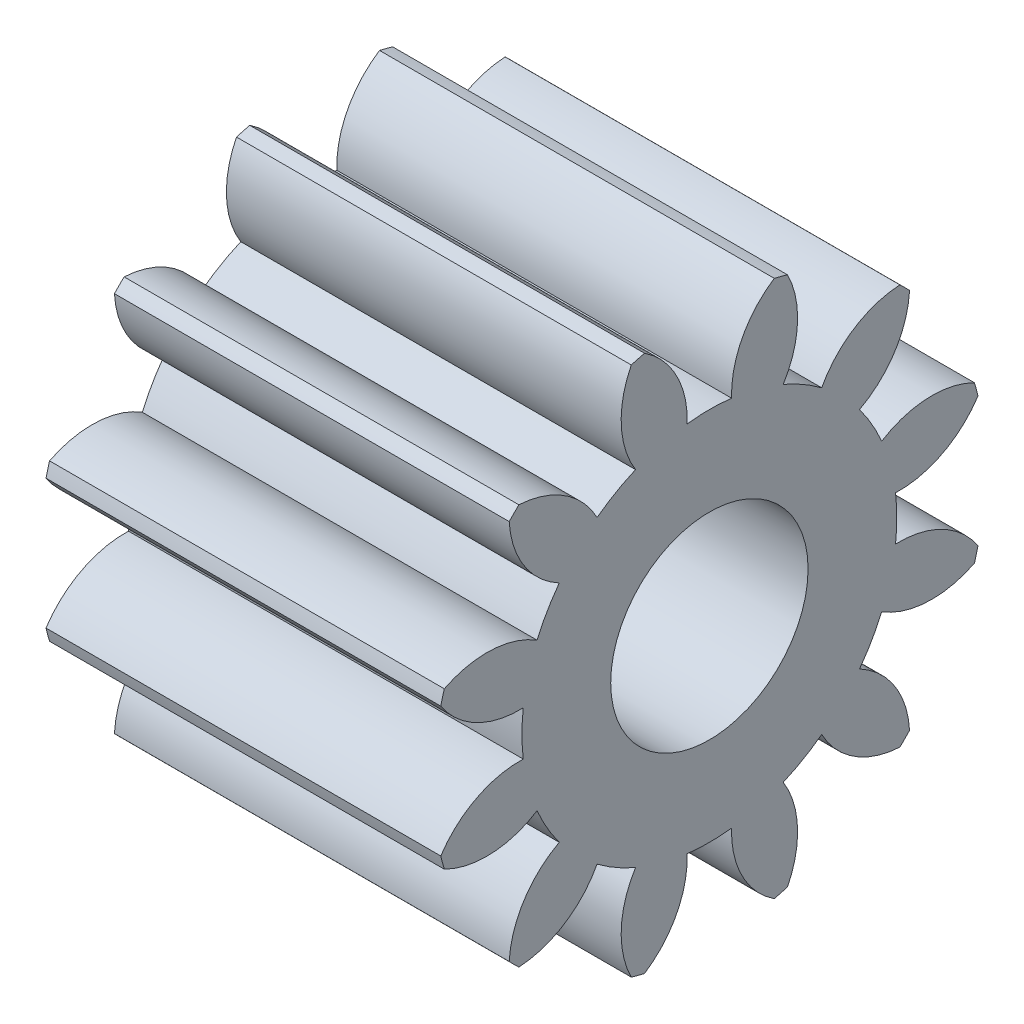
SolidWorks part; units mm, degrees
ref_plane "Plane1" through (0, 0, 0) normal (0, 0, 1) x (1, 0, 0)
ref_plane "Plane2" through (0, 0, 0) normal (0, 1, 0) x (1, 0, 0)
ref_plane "Plane3" through (0, 0, 0) normal (1, 0, 0) x (0, 0, -1)
sketch "HoldingSke" plane through (0, 0, 0) normal (0, 1, 0) x (1, 0, 0)
  line L0 (0, 0) -> (0.9781, -0.2079)
  line L1 (-15, 0) -> (100, 0) construction
  line L2 (0, 0) -> (-2.1039, 2.3779)
  line L3 (0, 0) -> (-11.863, 4.5341)
  line L4 (0, 0) -> (8.4473, 1.7955)
  line L5 (0, 0) -> (-46.8476, -17.4728)
  line L6 (0, 0) -> (-8.2896, -5.593)
  line L7 (-2.1039, 2.3779) -> (8.6586, 51.2059)
  line L8 (-76.2, 54.61) -> (-75.3, 54.61)
  line L9 (-71.009, 38.7566) -> (-53.1078, 45.2721)
  line L10 (-76.2, 71.12) -> (104.1128, 71.12)
  line L11 (0, 0) -> (-10, 0)
  line L12 (-76.2, 101.6) -> (-76.162, 101.6)
  line L13 (24.9733, 27.94) -> (52.9518, 28.4284)
  line L14 (24.9733, 27.94) -> (24.9743, 27.94)
  line L15 (24.9733, 27.94) -> (100.4006, 29.5858)
  line L16 (-63.627, -1) -> (-12.827, -1)
  circle A0 centre (0, 0) radius 2.5
  circle A1 centre (0, 0) radius 4.749
  circle A2 centre (0, 0) radius 37.5
  circle A3 centre (0, 0) radius 2.5
  dimension "MHD" = 9.498
  dimension "Hub_dia" = 75
  dimension "Bore" = 5
  dimension "MBD" = 5
  dimension "Num_teeth" = 12
  dimension "Pitch" = 1
  dimension "Overall_len" = 50
  dimension "Show_teeth" = 12
  dimension "Thickness" = 10
  dimension "OAL" = 50.0001
  dimension "T_dim" = 0.9
  dimension "Ap" = 20
  dimension "H" = 19.05
  dimension "Pitch_radius" = 180.3128
  dimension "Width" = 10
  dimension "Backlash" = 0.038
  dimension "Addendum_fac" = 1
  dimension "Dedendum_fac" = 1.25
  dimension "Clearance_fac" = 0.25
  dimension "Dedendum_add" = 0.001
  dimension "Module" = 1
sketch "BasProSke" plane through (0, 0, 0) normal (0, 1, 0) x (1, 0, 0)
  line L0 (-10, 0) -> (60, 0) construction
  line L1 (0, 0) -> (0, 7)
  line L2 (0, 0) -> (10, 0)
  line L3 (10, 0) -> (10, 7)
  line L4 (10, 7) -> (0, 7)
  dimension "Thickness" = 10
  dimension "Diameter" = 14
revolve "Base-Revolve" add sketch "BasProSke" angle 360 about L0
sketch "TooCutSke" plane through (0, 0, 0) normal (1, 0, 0) x (0, 0, -1)
  line L1 (0, 0) -> (0, 107) construction
  line L2 (0, 0) -> (-0.8496, 5.9395) construction
  line L3 (0, 0) -> (-3.0836, 11.5081) construction
  line L4 (-0.8496, 5.9395) -> (-1.5418, 5.7541) construction
  arc A0 (0.5622, 4.7156) -> (-0.5622, 4.7156) centre (0, 0) ccw
  arc A1 (1.6729, 6.8233) -> (-1.6729, 6.8233) centre (0, 0) ccw
  circle A2 centre (0, 0) radius 6 construction
  circle A3 centre (0, 0) radius 5.6382 construction
  arc A4 (-0.5622, 4.7156) -> (-1.6729, 6.8233) centre (-2.9608, 4.7982) ccw
  arc A5 (1.6729, 6.8233) -> (0.5622, 4.7156) centre (2.9608, 4.7982) ccw
  dimension "Root_dia" = 9.498
  dimension "Overcut_dia" = 14.0508
  dimension "Pitch_dia" = 12
  dimension "Base_dia" = 11.2763
  dimension "Flank_rad" = 2.4
  dimension "Half_ang" = 15
  dimension "Half_CT" = 0.7167
extrude "ToothCut" cut sketch "TooCutSke" along normal through all
fillet "Breaks" [suppressed] radius 0.02
fillet "RootFillets" [suppressed] radius 0.251
pattern_circular "TeethCuts" count 12 every 30 about axis through (-10, 0, 0) along (1, 0, 0) of "ToothCut", "RootFillets", "Breaks"
sketch "HubNeaOneSke" plane through (0, 0, 0) normal (-1, 0, 0) x (0, 0, 1)
  circle A0 centre (0, 0) radius 4.749
  dimension "Diameter" = 9.498
extrude "HubNearOne" [suppressed] add sketch "HubNeaOneSke" along normal blind 40.0001
sketch "HubNeaBotSke" plane through (0, 0, 0) normal (-1, 0, 0) x (0, 0, 1)
  circle A0 centre (0, 0) radius 4.749
  dimension "Diameter" = 9.498
extrude "HubNearBoth" [suppressed] add sketch "HubNeaBotSke" along normal blind 20
ref_plane "FarPln" through (10, 0, 0) normal (1, 0, 0) x (0, 0, -1)
sketch "HubFarSke" plane through (10, 0, 0) normal (1, 0, 0) x (0, 0, -1)
  circle A0 centre (0, 0) radius 4.749
  dimension "Diameter" = 9.498
extrude "HubFar" [suppressed] add sketch "HubFarSke" along normal blind 20
sketch "BorSke" plane through (0, 0, 0) normal (1, 0, 0) x (0, 0, -1)
  circle A0 centre (0, 0) radius 2.5
  dimension "Diameter" = 5
extrude "Bore" cut sketch "BorSke" along normal mid plane 100.0001
sketch "KeySke" plane through (0, 0, 0) normal (1, 0, 0) x (0, 0, -1)
  line L0 (-1, 0) -> (-1, 3.4)
  line L1 (-1, 3.4) -> (1, 3.4)
  line L2 (1, 3.4) -> (1, 0)
  line L3 (0, 0) -> (0, 34) construction
  line L4 (-1, 0) -> (1, 0)
  dimension "Offset" = 3.4
  dimension "Width" = 2
extrude "Keyway" [suppressed] cut sketch "KeySke" along normal mid plane 100.0001
pattern_circular "Keyway2" [suppressed] count 2 every 90 about axis through (-10, 0, 0) along (1, 0, 0)
equation "' \"Module@HoldingSke\" = 6.35"
equation "' \"Num_teeth@HoldingSke\" = 12"
equation "' \"Ap@HoldingSke\" =  20"
equation "' \"Ap@HoldingSke\" = 20"
equation "' \"Width@HoldingSke\" = 0.5 * 25.4"
equation "' \"Hub_dia@HoldingSke\"= 1 * 25.4"
equation "' \"Hub_dia@HoldingSke\" = 1 * 25.4"
equation "' \"Overall_len@HoldingSke\" = 1.0 * 25.4"
equation "' \"Bore@HoldingSke\" = 0.75 * 25.4"
equation "' \"T_dim@HoldingSke\" = 0.1 * 25.4"
equation "' \"Width@KeySke\" = 0.25 * 25.4"
equation "' \"Show_teeth@HoldingSke\" = 13"
equation "' \"Backlash@HoldingSke\" = 0.009 * 25.4"
equation "' \"Addendum_fac@HoldingSke\" = 1.0"
equation "' \"Dedendum_fac@HoldingSke\" = 1.25"
equation "' \"Dedendum_add@HoldingSke\" = 0.00005 * 25.4"
equation "' \"Clearance_fac@HoldingSke\" = 0.25"
equation "\"Pitch@HoldingSke\" = 1 / \"Module@HoldingSke\""
equation "\"Overcut_dia@TooCutSke\" = (\"Num_teeth@HoldingSke\" + 2 * \"Addendum_fac@HoldingSke\") / \"Pitch@HoldingSke\" + 0.002 * 25.4"
equation "\"Pitch_dia@TooCutSke\" = \"Num_teeth@HoldingSke\" / \"Pitch@HoldingSke\""
equation "\"Base_dia@TooCutSke\" = \"Num_teeth@HoldingSke\" / \"Pitch@HoldingSke\" * cos((\"Ap@HoldingSke\"  * 3.14159265 / 180))"
equation "\"Root_dia@TooCutSke\" = (\"Num_teeth@HoldingSke\" + 2) / \"Pitch@HoldingSke\" - 2 * (\"Addendum_fac@HoldingSke\" + \"Dedendum_fac@HoldingSke\") / \"Pitch@HoldingSke\" - \"Dedendum_add@HoldingSke\" * 2"
equation "\"Half_ang@TooCutSke\" = 180 / \"Num_teeth@HoldingSke\""
equation "\"Half_CT@TooCutSke\" = \"Num_teeth@HoldingSke\" / \"Pitch@HoldingSke\" * sin((3.14159265 / 2 / \"Num_teeth@HoldingSke\")) / 2 - 7 * \"Backlash@HoldingSke\" / 4"
equation "\"Flank_rad@TooCutSke\" = \"Num_teeth@HoldingSke\" / \"Pitch@HoldingSke\" / 5"
equation "\"Radius@RootFillets\" = \"Clearance_fac@HoldingSke\" / \"Pitch@HoldingSke\" + \"Dedendum_add@HoldingSke\""
equation "\"Break_rad@Breaks\" = 0.02 / \"Pitch@HoldingSke\""
equation "\"Thickness@HoldingSke\" = \"Width@HoldingSke\""
equation "\"OAL@HoldingSke\" = \"Thickness@HoldingSke\""
equation "\"MHD@HoldingSke\" = (\"Num_teeth@HoldingSke\" + 2) / \"Pitch@HoldingSke\" - 2 * (\"Addendum_fac@HoldingSke\" + \"Dedendum_fac@HoldingSke\")  / \"Pitch@HoldingSke\" - \"Dedendum_add@HoldingSke\" * 2"
equation "\"MBD@HoldingSke\" = (\"Num_teeth@HoldingSke\" + 2) / \"Pitch@HoldingSke\" - 2 * (\"Addendum_fac@HoldingSke\" + \"Dedendum_fac@HoldingSke\")  / \"Pitch@HoldingSke\" - \"Dedendum_add@HoldingSke\" * 2 - 0.002 * 25.4"
equation "\"MHD@HoldingSke\" = ((sgn( \"MHD@HoldingSke\" - \"Hub_dia@HoldingSke\" )-1)*( \"MHD@HoldingSke\" - \"Hub_dia@HoldingSke\" ))/-2+ \"Hub_dia@HoldingSke\""
equation "\"MBD@HoldingSke\" = ((sgn( \"MBD@HoldingSke\" - \"Bore@HoldingSke\" )-1)*( \"MBD@HoldingSke\" - \"Bore@HoldingSke\" ))/-2+ \"Bore@HoldingSke\""
equation "\"OAL@HoldingSke\" = ((sgn( \"OAL@HoldingSke\" - \"Overall_len@HoldingSke\" )+1)*( \"OAL@HoldingSke\" - \"Overall_len@HoldingSke\" ))/2 + \"Overall_len@HoldingSke\" + 0.000002 * 25.4"
equation "\"Num_teeth@TeethCuts\" = int( \"Show_teeth@HoldingSke\" ) + 1"
equation "\"Num_teeth@TeethCuts\" = ((sgn( \"Num_teeth@TeethCuts\" - \"Num_teeth@HoldingSke\" )-1)*( \"Num_teeth@TeethCuts\" - \"Num_teeth@HoldingSke\" ))/-2+ \"Num_teeth@HoldingSke\""
equation "\"Num_teeth@TeethCuts\" = ((sgn( \"Num_teeth@TeethCuts\" - 2.0)+1)*( \"Num_teeth@TeethCuts\" - 2.0))/2 +2.0"
equation "\"Angle@TeethCuts\" = 360.0 / \"Num_teeth@HoldingSke\""
equation "\"Diameter@BasProSke\" = (\"Num_teeth@HoldingSke\" + 2 * \"Addendum_fac@HoldingSke\") / \"Pitch@HoldingSke\""
equation "\"Thickness@BasProSke\"  = \"Thickness@HoldingSke\""
equation "' \"Fillet_rad@BasProSke\" =  \"Thickness@HoldingSke\" * 0.05"
equation "' \"Fillet_rad@BasProSke\" = \"Thickness@HoldingSke\" * 0.05"
equation "\"MHD@HoldingSke\" = ((sgn( \"MHD@HoldingSke\" - \"Root_dia@TooCutSke\" )-1)*( \"MHD@HoldingSke\" - \"Root_dia@TooCutSke\" ))/-2+ \"Root_dia@TooCutSke\""
equation "\"Diameter@HubNeaOneSke\" = \"MHD@HoldingSke\""
equation "\"Length@HubNearOne\" = \"OAL@HoldingSke\" - \"Thickness@BasProSke\""
equation "\"Diameter@HubNeaBotSke\" = \"MHD@HoldingSke\""
equation "\"Length@HubNearBoth\" = ( \"OAL@HoldingSke\" - \"Thickness@BasProSke\" ) / 2.0"
equation "\"Thickness@FarPln\" = \"Thickness@BasProSke\""
equation "\"Diameter@HubFarSke\" = \"MHD@HoldingSke\""
equation "\"Length@HubFar\" = ( \"OAL@HoldingSke\" - \"Thickness@BasProSke\" ) / 2.0"
equation "\"Diameter@BorSke\" = \"MBD@HoldingSke\""
equation "\"D1@Bore\" = \"OAL@HoldingSke\" * 2.0"
equation "\"D1@Keyway\" = \"OAL@HoldingSke\" * 2.0"
equation "\"Offset@KeySke\" = \"T_dim@HoldingSke\" + \"MBD@HoldingSke\" / 2.0"
